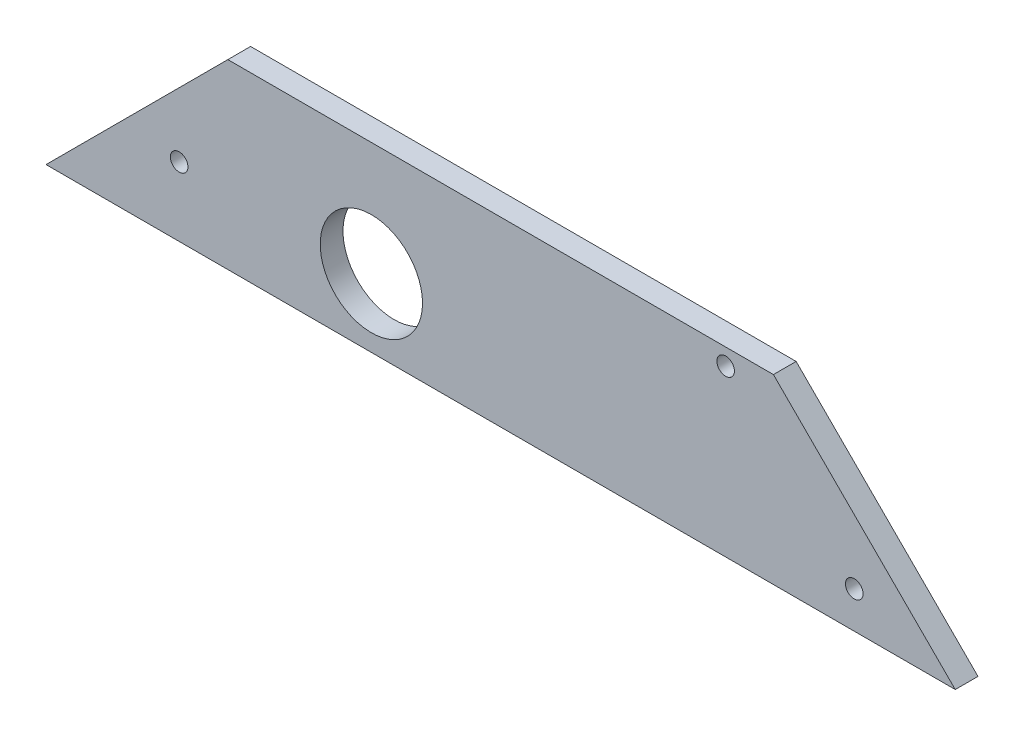
SolidWorks part; units mm, degrees
ref_plane "Front Plane" through (0, 0, 0) normal (0, 0, 1) x (1, 0, 0)
ref_plane "Top Plane" through (0, 0, 0) normal (0, 1, 0) x (1, 0, 0)
ref_plane "Right Plane" through (0, 0, 0) normal (1, 0, 0) x (0, 0, -1)
sketch "Sketch1" plane through (0, 0, 0) normal (0, 0, 1) x (1, 0, 0)
  line L0 (-76.2, 29.1622) -> (-127, -21.6378)
  line L1 (-76.2, 29.1622) -> (76.2, 29.1622)
  line L2 (-127, -21.6378) -> (127, -21.6378)
  line L3 (127, -21.6378) -> (76.2, 29.1622)
  point P0 (0, 0)
  point P1 (0, -21.6378)
  dimension "D1" = 135
  dimension "D2" = 254
  dimension "D3" = 50.8
  dimension "D4" = 135
extrude "Boss-Extrude1" add sketch "Sketch1" along normal mid plane 6.35
sketch "Sketch2" plane through (0, 0, 3.175) normal (0, 0, 1) x (1, 0, 0)
  line L0 (-127, -21.6378) -> (127, -21.6378) construction
  line L3 (-76.2, 29.1622) -> (-127, -21.6378) construction
  circle A0 centre (-36.108, -2.5878) radius 14.2875
  dimension "D1" = 19.05
  dimension "D2" = 28.575
  dimension "D3" = 50.8
extrude "Cut-Extrude1" cut sketch "Sketch2" against normal through all
sketch "Sketch8" plane through (0, 0, 3.175) normal (0, 0, 1) x (1, 0, 0)
  line L0 (0, 105.3622) -> (-327.0287, -221.6666) construction
  line L1 (0, 69.4411) -> (279.7642, -210.3231) construction
  line L2 (76.2, 29.1622) -> (297.7247, -192.3626) construction
  line L3 (0, 69.4411) -> (-309.0682, -239.6271) construction
  line L4 (76.2, 29.1622) -> (0, 105.3622) construction
  line L5 (14.5597, 84.0009) -> (-309.0682, -239.6271) construction
  line L6 (58.2395, 11.2016) -> (279.7642, -210.3231) construction
  line L7 (-3.4008, 101.9614) -> (-327.0287, -221.6666) construction
  line L8 (98.7828, -11.3812) -> (62.8618, 24.5398) construction
  line L9 (-76.2, 29.1622) -> (-127, -21.6378) construction
  point P2 (62.8618, 24.5398)
  point P6 (98.7828, -11.3812)
  point P16 (-89.8026, -2.4009)
  dimension "D1" = 25.4
  dimension "D2" = 25.4
  dimension "D3" = 12.7
  dimension "D4" = 101.6
  dimension "D5" = 152.4
  dimension "D6" = 12.7
  dimension "D7" = 12.7
  dimension "D8" = 139.7
hole_wizard "#10 (0.1935) Diameter Hole2" positions "3DSketch1" profile "Sketch9" hole size "#10" standard "ANSI Inch" end condition through all
sketch3d "3DSketch1"
  line L0 (-127, -21.6378, 3.175) -> (-76.2, 29.1622, 3.175) construction
  line L2 (-76.2, 29.1622, 3.175) -> (0, 105.3622, 3.175) construction
  line L3 (0, 105.3622, 3.175) -> (145.7507, -40.3886, 3.175) construction
  line L4 (76.2, 29.1622, 3.175) -> (297.7247, -192.3626, 3.175) construction
  line L5 (145.7507, -40.3886, 3.175) -> (127.7902, -58.3491, 3.175) construction
  line L6 (0, 69.4411, 3.175) -> (279.7642, -210.3231, 3.175) construction
  line L7 (127.7902, -58.3491, 3.175) -> (0, 69.4411, 3.175) construction
  line L8 (0, 69.4411, 3.175) -> (-116.7666, -47.3254, 3.175) construction
  line L9 (0, 69.4411, 3.175) -> (-309.0682, -239.6271, 3.175) construction
  line L10 (-116.7666, -47.3254, 3.175) -> (-134.7271, -29.3649, 3.175) construction
  line L11 (0, 105.3622, 3.175) -> (-327.0287, -221.6666, 3.175) construction
  line L12 (-134.7271, -29.3649, 3.175) -> (-127, -21.6378, 3.175) construction
  point P0 (62.8618, 24.5398, 3.175)
  point P4 (98.7828, -11.3812, 3.175)
  point P8 (-89.8026, -2.4009, 3.175)
  dimension "D1" = 12.7
  dimension "D2" = 139.7
  dimension "D3" = 12.7
  dimension "D6" = 12.7
  dimension "D4" = 101.6
  dimension "D5" = 50.8
sketch "Sketch9" plane through (62.8618, 24.5398, 3.175) normal (1, 0, 0) x (0, -1, 0)
  line L0 (0, 0) -> (0, 6.35)
  line L1 (0, 6.35) -> (2.4574, 6.35)
  line L2 (2.4574, 6.35) -> (2.4574, 0)
  line L5 (2.4574, 0) -> (0, 0)
  line L11 (0, -6.35) -> (0, 107.95) construction
  dimension "Thru Hole Dia." = 4.9149
  dimension "Thru Hole Depth" = 6.35
